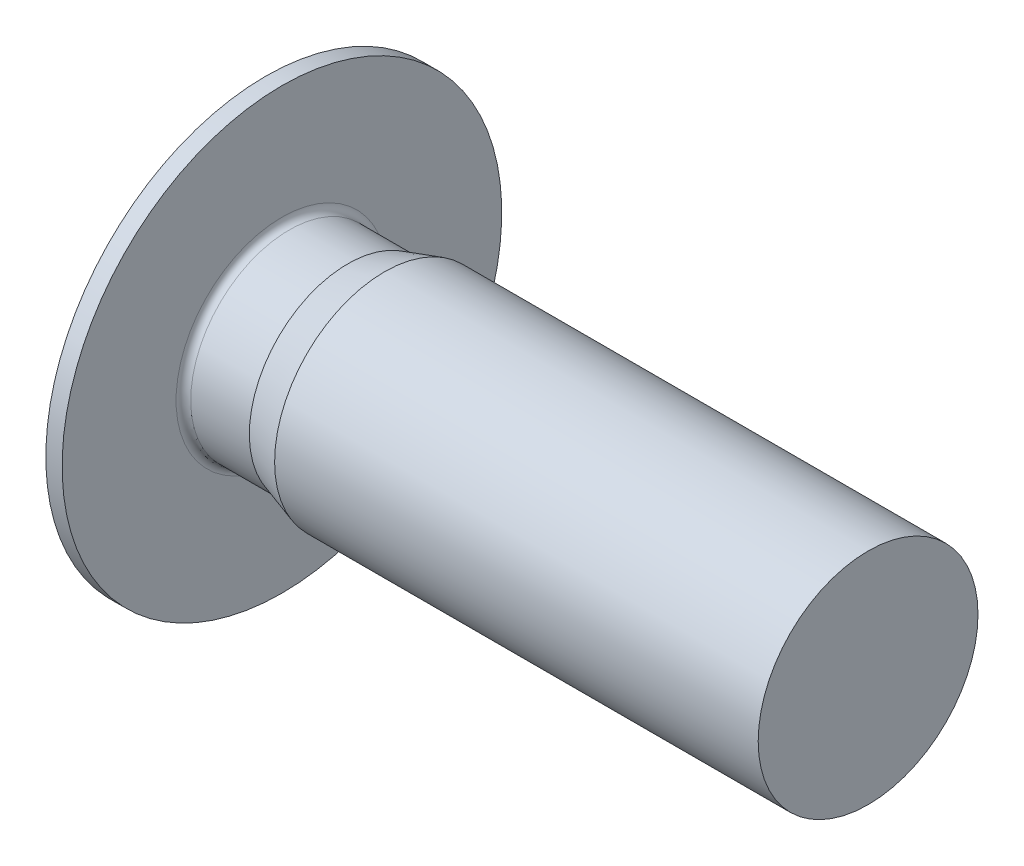
SolidWorks part; units mm, degrees
material "SCM435"
ref_plane "Front Plane" through (0, 0, 0) normal (0, 0, 1) x (1, 0, 0)
ref_plane "Top Plane" through (0, 0, 0) normal (0, 1, 0) x (1, 0, 0)
ref_plane "Right Plane" through (0, 0, 0) normal (1, 0, 0) x (0, 0, -1)
sketch "Sketch1" plane through (0, 0, 0) normal (0, 0, 1) x (1, 0, 0)
  line L0 (-0.8, 0) -> (8, 0) construction
  line L1 (-0.8, 0) -> (-0.8, 2)
  line L2 (-0.2226, 3) -> (0, 3)
  line L3 (0, 3) -> (0, 1.345)
  line L4 (1.4, 1.5) -> (8, 1.5)
  line L5 (8, 1.5) -> (8, 0)
  line L6 (8, 0) -> (-0.8, 0)
  line L7 (1.4, 1.5) -> (0.9, 1.345)
  line L8 (0.9, 1.345) -> (0, 1.345)
  line L9 (-0.2226, 3) -> (-0.8, 2)
  line L10 (-0.8, 0) -> (8, 0) construction
  dimension "A" = 6
  dimension "M" = 3
  dimension "L" = 8
  dimension "MSM_1" = 4
  dimension "E_s" = 1.4
  dimension "E" = 0.8
  dimension "FIX_1" = 30
  dimension "MSM_2" = 2.69
  dimension "MSM_3" = 0.5
revolve "Revolve1" add sketch "Sketch1" angle 360 about L0
cosmetic thread "Thread1" parameters "ATL_1"=6.6, "ATD"=2.459
fillet "Fillet1" radius 0.1 1 edges at (0, -1.345, 0)
sketch "Sketch2" plane through (-0.8, 0, 0) normal (-1, 0, 0) x (0, 0, 1)
  line L1 (0, 0.866) -> (-0.75, 0.433)
  line L2 (-0.75, 0.433) -> (-0.75, -0.433)
  line L3 (-0.75, -0.433) -> (0, -0.866)
  line L4 (0, -0.866) -> (0.75, -0.433)
  line L5 (0.75, -0.433) -> (0.75, 0.433)
  line L6 (0.75, 0.433) -> (0, 0.866)
  circle A0 centre (0, 0) radius 0.75 construction
extrude "Cut-Extrude1" cut sketch "Sketch2" against normal blind 2
sketch "Sketch3" plane through (0, 0, 0) normal (0, 0, 1) x (1, 0, 0)
  line L0 (1.2, 0) -> (1.6506, 0) construction
  line L1 (1.2, 0) -> (1.2, 0.75)
  line L2 (1.2, 0.75) -> (1.6506, 0)
  line L3 (1.6506, 0) -> (1.2, 0)
  line L5 (1.2, 0.433) -> (1.2, -0.433) construction
  dimension "FIX_3" = 59
revolve "Cut-Revolve1" cut sketch "Sketch3" angle 360 about L0
equation "\"ATL_1@Thread1\" = \"L@Sketch1\" - \"E_s@Sketch1\""
